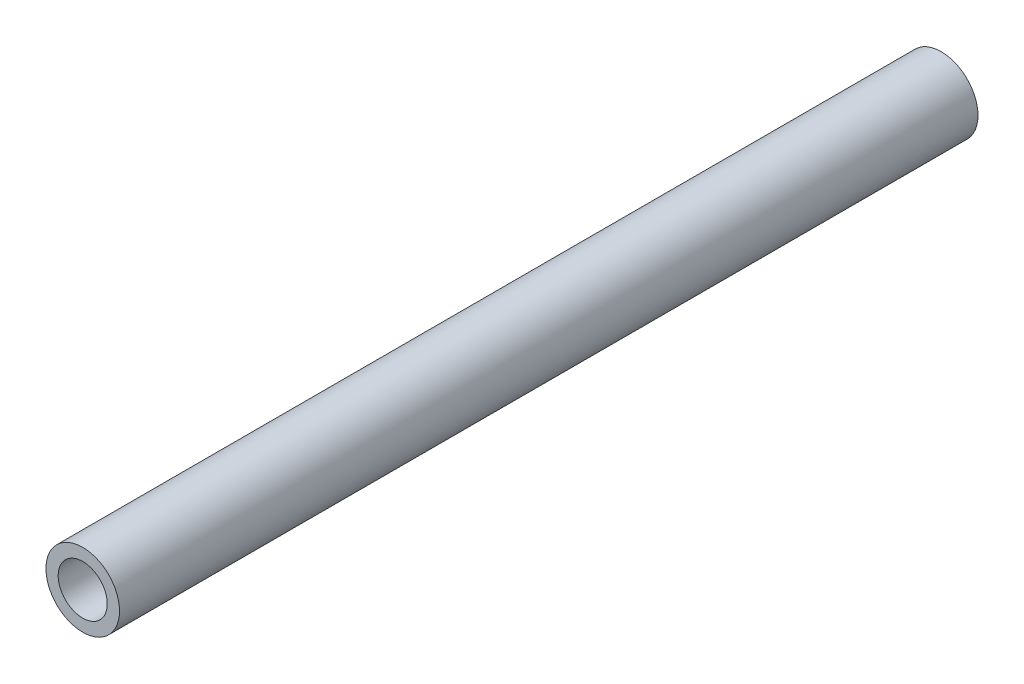
SolidWorks part; units mm, degrees
ref_plane "Front Plane" through (0, 0, 0) normal (0, 0, 1) x (1, 0, 0)
ref_plane "Top Plane" through (0, 0, 0) normal (0, 1, 0) x (1, 0, 0)
ref_plane "Right Plane" through (0, 0, 0) normal (1, 0, 0) x (0, 0, -1)
sketch "Sketch1" plane through (0, 0, 0) normal (0, 0, 1) x (1, 0, 0)
  circle A0 centre (0, 0) radius 3
  dimension "D1" = 6
extrude "Boss-Extrude1" add sketch "Sketch1" along normal blind 70
sketch "Sketch2" plane through (0, 0, 70) normal (0, 0, 1) x (1, 0, 0)
  circle A0 centre (0, 0) radius 2
  dimension "D1" = 4
extrude "Cut-Extrude1" cut sketch "Sketch2" against normal blind 7
sketch "Sketch3" plane through (0, 0, 0) normal (0, 0, -1) x (-1, 0, 0)
  circle A0 centre (0, 0) radius 2
  dimension "D1" = 4
extrude "Cut-Extrude2" cut sketch "Sketch3" against normal blind 7
